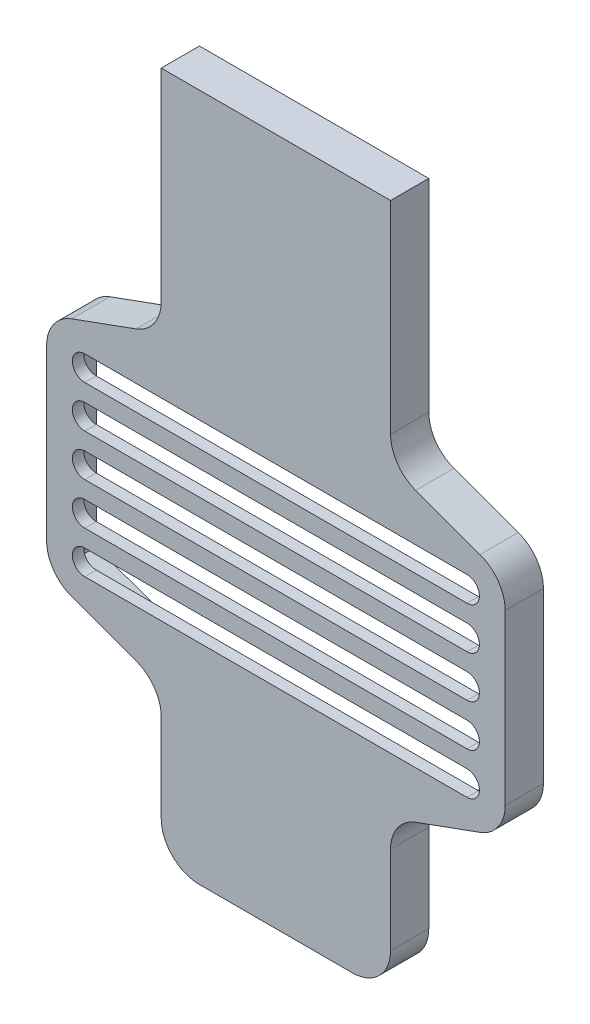
SolidWorks part; units mm, degrees
material "Сплав 2024"
ref_plane "Спереди" through (0, 0, 0) normal (0, 0, 1) x (1, 0, 0)
ref_plane "Сверху" through (0, 0, 0) normal (0, 1, 0) x (1, 0, 0)
ref_plane "Справа" through (0, 0, 0) normal (1, 0, 0) x (0, 0, -1)
sketch "Эскиз1" plane through (0, 0, 0) normal (0, 0, 1) x (1, 0, 0)
  line L0 (31.6276, -80) -> (0, -80) construction
  line L1 (0, 0) -> (60, 0)
  line L2 (0, 0) -> (0, -180) construction
  line L3 (0, -180) -> (60, -180)
  line L4 (60, 0) -> (60, -60)
  line L5 (30, 0) -> (30, -180) construction
  line L6 (0, -60) -> (-30, -70.9191)
  line L7 (-30, -70.9191) -> (-30, -129.0809)
  line L8 (-30, -129.0809) -> (0, -140)
  line L9 (0, 0) -> (0, -60)
  line L10 (0, -140) -> (0, -180)
  line L15 (60, -140) -> (60, -180)
  line L16 (90, -129.0809) -> (60, -140)
  line L17 (90, -70.9191) -> (90, -129.0809)
  line L18 (60, -60) -> (90, -70.9191)
  dimension "D1" = 40
  dimension "D2" = 180
  dimension "D3" = 80
  dimension "D4" = 60
  dimension "D5" = 60
  dimension "D6" = 90
  dimension "D7" = 110
  dimension "D8" = 110
extrude "Бобышка-Вытянуть1" add sketch "Эскиз1" along normal blind 10
fillet "Скругление1" radius 10 10 edges at (60, -60, 5) (90, -70.9191, 5) (90, -129.0809, 5) (60, -140, 5) (60, -180, 5) (0, -60, 5) (-30, -70.9191, 5) (0, -140, 5) (-30, -129.0809, 5) (0, -180, 5)
sketch "Эскиз2" plane through (0, 10, 10) normal (0, 0, 1) x (-1, 0, 0)
  line L0 (20, 88) -> (-80, 88) construction
  line L1 (-60, 10) -> (0, 10) construction
  line L2 (-30, 190) -> (-30, 10) construction
  line L3 (20, 102.25) -> (-80, 102.25)
  line L4 (-10, 190) -> (-50, 190) construction
  line L6 (20, 91.25) -> (-80, 91.25)
  line L7 (20, 91.25) -> (20, 84.75) construction
  line L8 (20, 84.75) -> (-80, 84.75)
  line L9 (20, 95.75) -> (-80, 95.75)
  line L10 (-80, 91.25) -> (-80, 84.75) construction
  line L11 (20, 91.25) -> (-80, 84.75) construction
  line L12 (20, 84.75) -> (-80, 91.25) construction
  line L13 (0, 10) -> (-60, 10) construction
  line L15 (20, 113.25) -> (-80, 113.25)
  line L16 (20, 106.75) -> (-80, 106.75)
  line L17 (20, 124.25) -> (-80, 124.25)
  line L18 (20, 117.75) -> (-80, 117.75)
  line L19 (20, 135.25) -> (-80, 135.25)
  line L20 (20, 128.75) -> (-80, 128.75)
  line L21 (-80, 138.1089) -> (-80, 88) construction
  line L22 (30, 80.9191) -> (30, 139.0809) construction
  line L23 (-90, 80.9191) -> (-90, 139.0809) construction
  arc A0 (20, 91.25) -> (20, 84.75) centre (20, 88) cw
  arc A1 (-80, 91.25) -> (-80, 84.75) centre (-80, 88) ccw
  arc A2 (-80, 102.25) -> (-80, 95.75) centre (-80, 99) ccw
  arc A3 (20, 102.25) -> (20, 95.75) centre (20, 99) cw
  arc A4 (-80, 113.25) -> (-80, 106.75) centre (-80, 110) ccw
  arc A5 (20, 113.25) -> (20, 106.75) centre (20, 110) cw
  arc A6 (-80, 124.25) -> (-80, 117.75) centre (-80, 121) ccw
  arc A7 (20, 124.25) -> (20, 117.75) centre (20, 121) cw
  arc A8 (-80, 135.25) -> (-80, 128.75) centre (-80, 132) ccw
  arc A9 (20, 135.25) -> (20, 128.75) centre (20, 132) cw
  point P8 (-30, 88)
  dimension "D3" = 10
  dimension "D1" = 78
  dimension "D2" = 6.5
  dimension "D4" = 10
  dimension "D6" = 50.5
  dimension "D5" = 5
extrude "Вырез-Вытянуть1" cut sketch "Эскиз2" against normal through all
sketch "Эскиз3" plane through (0, 0, 0) normal (0, 0, -1) x (-1, 0, 0)
  line L0 (30, -70.9191) -> (30, -129.0809) construction
  line L1 (0, -60) -> (30, -70.9191) construction
  line L2 (30, -129.0809) -> (0, -140) construction
  line L3 (-60, -60) -> (-90, -70.9191) construction
  line L4 (-90, -70.9191) -> (-90, -129.0809) construction
  line L5 (-90, -129.0809) -> (-60, -140) construction
  line L8 (-57, -137.8994) -> (-3, -137.8994)
  line L9 (0, -180) -> (-60, -180) construction
  line L10 (-57, -62.1006) -> (-3, -62.1006)
  line L11 (0, 0) -> (-60, 0) construction
  line L138 (27, -73.0197) -> (-3, -62.1006)
  line L139 (27, -126.9803) -> (27, -73.0197)
  line L140 (-3, -137.8994) -> (27, -126.9803)
  line L141 (-87, -73.0197) -> (-87, -126.9803)
  line L142 (-87, -126.9803) -> (-57, -137.8994)
  line L143 (-57, -62.1006) -> (-87, -73.0197)
  dimension "D2" = 3
  dimension "D1" = 3
  dimension "D3" = 3
  dimension "D4" = 3
  dimension "D5" = 3
  dimension "D6" = 3
  dimension "D7" = 42.1006
  dimension "D8" = 62.1006
extrude "Вырез-Вытянуть2" cut sketch "Эскиз3" against normal blind 7
sketch "Эскиз4" plane through (0, 0, 0) normal (0, 0, -1) x (-1, 0, 0)
  line L0 (-30, 0) -> (-30, -180) construction
  line L1 (-40.1, -24.75) -> (-19.9, -24.75)
  line L2 (-40.1, -24.75) -> (-40.1, -64.75)
  line L3 (-40.1, -64.75) -> (-19.9, -64.75)
  line L4 (-19.9, -24.75) -> (-19.9, -64.75)
  line L5 (-40.1, -24.75) -> (-19.9, -64.75) construction
  line L6 (-40.1, -64.75) -> (-19.9, -24.75) construction
  line L9 (-80, -74.75) -> (20, -74.75) construction
  point P0 (-30, -44.75)
  dimension "D1" = 20.2
  dimension "D2" = 40
  dimension "D3" = 10
extrude "Вырез-Вытянуть3" cut sketch "Эскиз4" against normal up to surface (7 mm away) up to face at (30, -89, 7)
sketch "Эскиз6" plane through (0, 0, 0) normal (0, 0, -1) x (-1, 0, 0)
  line L0 (-60, -140) -> (-60, -180) construction
  line L1 (-57, -135) -> (-50.7, -135) construction
  line L2 (-57, -135) -> (-57, -170)
  line L3 (-57, -170) -> (-50.7, -170) construction
  line L4 (-50.7, -135) -> (-50.7, -170)
  line L5 (-57, -135) -> (-50.7, -170) construction
  line L6 (-57, -170) -> (-50.7, -135) construction
  line L7 (0, -180) -> (-60, -180) construction
  line L8 (-47.46, -135) -> (-47.46, -170)
  line L9 (-41.16, -135) -> (-41.16, -170)
  line L10 (-47.46, -135) -> (-41.16, -135) construction
  line L11 (-47.46, -170) -> (-41.16, -170) construction
  line L12 (-47.46, -135) -> (-41.16, -170) construction
  line L13 (-37.92, -135) -> (-37.92, -170)
  line L14 (-31.62, -135) -> (-31.62, -170)
  line L15 (-37.92, -135) -> (-31.62, -135) construction
  line L16 (-37.92, -170) -> (-31.62, -170) construction
  line L17 (-37.92, -135) -> (-31.62, -170) construction
  line L18 (-28.38, -135) -> (-28.38, -170)
  line L19 (-22.08, -135) -> (-22.08, -170)
  line L20 (-28.38, -135) -> (-22.08, -135) construction
  line L21 (-28.38, -170) -> (-22.08, -170) construction
  line L22 (-28.38, -135) -> (-22.08, -170) construction
  line L23 (-18.84, -135) -> (-18.84, -170)
  line L24 (-12.54, -135) -> (-12.54, -170)
  line L25 (-18.84, -135) -> (-12.54, -135) construction
  line L26 (-18.84, -170) -> (-12.54, -170) construction
  line L27 (-18.84, -135) -> (-12.54, -170) construction
  line L28 (-9.3, -135) -> (-9.3, -170)
  line L29 (-3, -135) -> (-3, -170)
  line L30 (-9.3, -135) -> (-3, -135) construction
  line L31 (-9.3, -170) -> (-3, -170) construction
  line L32 (-9.3, -135) -> (-3, -170) construction
  line L33 (0, -140) -> (0, -180) construction
  line L34 (-6.15, -170) -> (-53.85, -170) construction
  arc A0 (-50.7, -135) -> (-57, -135) centre (-53.85, -135) ccw
  arc A1 (-50.7, -170) -> (-57, -170) centre (-53.85, -170) cw
  arc A2 (-41.16, -135) -> (-47.46, -135) centre (-44.31, -135) ccw
  arc A3 (-41.16, -170) -> (-47.46, -170) centre (-44.31, -170) cw
  arc A4 (-31.62, -135) -> (-37.92, -135) centre (-34.77, -135) ccw
  arc A5 (-31.62, -170) -> (-37.92, -170) centre (-34.77, -170) cw
  arc A6 (-22.08, -135) -> (-28.38, -135) centre (-25.23, -135) ccw
  arc A7 (-22.08, -170) -> (-28.38, -170) centre (-25.23, -170) cw
  arc A8 (-12.54, -135) -> (-18.84, -135) centre (-15.69, -135) ccw
  arc A9 (-12.54, -170) -> (-18.84, -170) centre (-15.69, -170) cw
  arc A10 (-3, -135) -> (-9.3, -135) centre (-6.15, -135) ccw
  arc A11 (-3, -170) -> (-9.3, -170) centre (-6.15, -170) cw
  point P0 (-53.85, -152.5)
  point P12 (-44.31, -152.5)
  point P19 (-34.77, -152.5)
  point P26 (-25.23, -152.5)
  point P33 (-15.69, -152.5)
  point P40 (-6.15, -152.5)
  dimension "D1" = 6.3
  dimension "D2" = 35
  dimension "D3" = 3
  dimension "D4" = 10
  dimension "D6" = 3
  dimension "D5" = 6
extrude "Вырез-Вытянуть4" cut sketch "Эскиз6" against normal up to surface (7 mm away) up to face at (30, -81.1418, 7)
equation "\"D6@Эскиз1\"=\"D5@Эскиз1\"+30"
